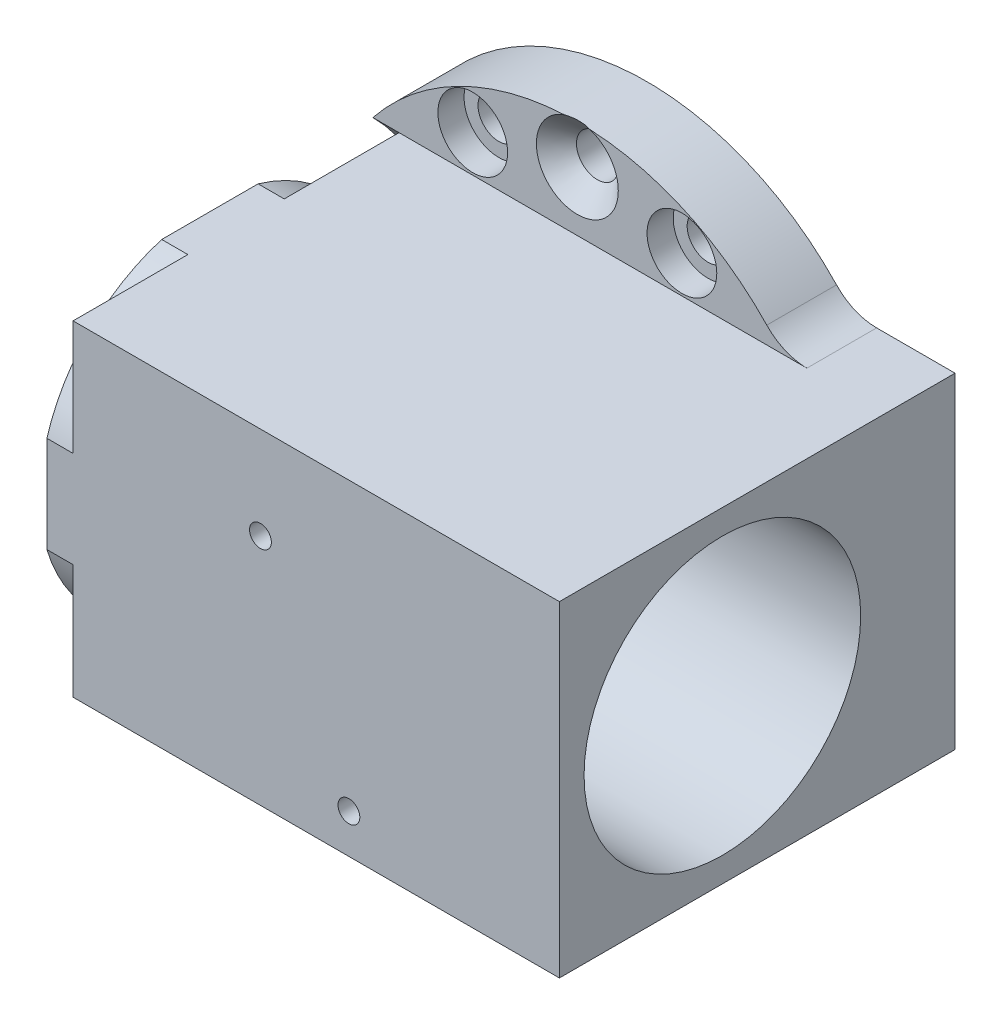
SolidWorks part; units mm, degrees
material "6061 Alloy"
ref_plane "Front" through (0, 0, 0) normal (0, 0, 1) x (1, 0, 0)
ref_plane "Top" through (0, 0, 0) normal (0, 1, 0) x (1, 0, 0)
ref_plane "Right" through (0, 0, 0) normal (1, 0, 0) x (0, 0, -1)
ref_plane "Plane1" through (0, 0, 8) normal (0, 0, 1) x (1, 0, 0)
sketch "Sketch1" plane through (0, 0, 8) normal (0, 0, 1) x (1, 0, 0)
  line L0 (-23.4587, 18.7) -> (-23.4587, -18.7)
  line L1 (23.4587, -18.7) -> (35.3413, -18.7)
  line L2 (35.3413, -18.7) -> (35.3413, 18.7)
  line L3 (35.3413, 18.7) -> (23.4587, 18.7)
  arc A0 (-23.4587, -18.7) -> (23.4587, -18.7) centre (0, 0) ccw
  arc A1 (23.4587, 18.7) -> (-23.4587, 18.7) centre (0, 0) ccw
extrude "Boss-Extrude1" add sketch "Sketch1" against normal blind 8
ref_plane "Plane2" through (-23.4587, 0, 0) normal (-1, 0, 0) x (0, -1, 0)
ref_plane "Plane3" through (-20.4587, 0, 0) normal (1, 0, 0) x (0, 0, -1)
sketch "Sketch3" plane through (-20.4587, 0, 0) normal (1, 0, 0) x (0, 0, -1)
  line L0 (-8, 18.7) -> (-8, -18.7)
  arc A0 (-8, -18.7) -> (-8, 18.7) centre (-26.7, 0) ccw
extrude "Cut-Extrude1" cut sketch "Sketch3" against normal up to surface up to plane "Plane2"
sketch "Sketch4" plane through (0, 0, 8) normal (0, 0, 1) x (1, 0, 0)
  line L0 (-20.4587, 18.7) -> (35.3413, 18.7)
  line L1 (35.3413, 18.7) -> (35.3413, -18.7)
  line L2 (35.3413, -18.7) -> (-20.4587, -18.7)
  line L3 (-20.4587, -18.7) -> (-20.4587, 18.7)
extrude "Boss-Extrude2" add sketch "Sketch4" along normal blind 37.4
sketch "Sketch5" plane through (-20.4587, 0, 0) normal (-1, 0, 0) x (0, 0, 1)
  line L0 (45.4, 18.7) -> (45.4, -18.7)
  line L1 (45.4, -18.7) -> (21.1719, -18.7)
  line L2 (21.1719, 18.7) -> (45.4, 18.7)
  arc A0 (21.1719, -18.7) -> (21.1719, 18.7) centre (26.7, 0) cw
extrude "Boss-Extrude3" add sketch "Sketch5" along normal blind 3
sketch "Sketch6" plane through (-23.4587, 0, 0) normal (-1, 0, 0) x (0, 0, 1)
  line L0 (45.4, -18.7) -> (45.4, -5.5281)
  line L1 (32.2281, -18.7) -> (45.4, -18.7)
  arc A0 (45.4, -5.5281) -> (32.2281, -18.7) centre (26.7, 0) cw
extrude "Cut-Extrude2" cut sketch "Sketch6" against normal blind 3
sketch "Sketch7" plane through (-23.4587, 0, 0) normal (-1, 0, 0) x (0, 0, 1)
  line L0 (45.4, 18.7) -> (32.2281, 18.7)
  line L1 (45.4, 5.5281) -> (45.4, 18.7)
  arc A0 (32.2281, 18.7) -> (45.4, 5.5281) centre (26.7, 0) cw
extrude "Cut-Extrude3" cut sketch "Sketch7" against normal blind 3
ref_plane "Plane4" through (0, 0, 26.7) normal (0, 0, 1) x (1, 0, 0)
sketch "Sketch8" plane through (0, 0, 26.7) normal (0, 0, 1) x (1, 0, 0)
  line L0 (-23.4587, 15.8686) -> (-23.4587, 0)
  line L1 (-23.4587, 0) -> (35.3413, 0)
  line L2 (35.3413, 0) -> (35.3413, 15.8687)
  line L3 (35.3413, 15.8687) -> (9.9413, 15.8687)
  line L4 (9.9413, 15.8687) -> (9.9413, 13.5)
  line L5 (9.9413, 13.5) -> (1.9413, 13.5)
  line L6 (1.9413, 13.5) -> (1.9413, 15.8686)
  line L7 (1.9413, 15.8686) -> (-23.4587, 15.8686)
  line L8 (-23.4587, 0) -> (35.3413, 0) construction
revolve "Cut-Revolve1" cut sketch "Sketch8" angle 360 about L8
hole_wizard "M4x0.7 Tapped Hole1" positions "Sketch10" profile "Sketch9" tap size "M4x0.7" standard "ANSI Metric"
sketch "Sketch10" plane through (0, -18.7, 0) normal (0, -1, 0) x (-1, 0, 0)
  point P0 (12.4587, -39.4)
  point P1 (-29.4413, -39.4)
  point P2 (-29.4413, -5.9)
sketch "Sketch9" plane through (-12.4587, -18.7, 39.4) normal (1, 0, 0) x (0, 0, -1)
  line L0 (0, 0) -> (0, 6.9914)
  line L1 (0, 6.9914) -> (1.65, 6)
  line L2 (1.65, 6) -> (1.65, 0)
  line L5 (1.65, 0) -> (0, 0)
  line L10 (0, 6.9914) -> (-1.65, 6) construction
  line L11 (0, -6.35) -> (0, 107.95) construction
  dimension "Tap Drill Dia." = 3.3
  dimension "Tap Drill Depth" = 6
  dimension "Drill Angle" = 118
hole_wizard "CSK for M4 Flat Head Machine Screw1" positions "Sketch12" profile "Sketch11" countersink size "M4" standard "ANSI Metric" end condition through all
sketch "Sketch12" plane through (0, 0, 8) normal (0, 0, 1) x (1, 0, 0)
  point P0 (0, -25.5)
  point P1 (0, 25.5)
sketch "Sketch11" plane through (0, -25.5, 8) normal (1, 0, 0) x (0, -1, 0)
  line L0 (0, 0) -> (0, 8)
  line L1 (0, 8) -> (2.4, 8)
  line L2 (2.4, 8) -> (2.4, 2.3)
  line L3 (2.4, 2.3) -> (4.7, 0)
  line L5 (4.7, 0) -> (0, 0)
  line L6 (-2.4, 2.3) -> (-4.7, 0) construction
  line L11 (0, -6.35) -> (0, 107.95) construction
  dimension "Thru Hole Dia." = 4.8
  dimension "Thru Hole Depth" = 8
  dimension "Near C'Sink Dia." = 9.4
  dimension "Near C'Sink Angle" = 90
hole_wizard "CBORE for M4 SHCS1" positions "Sketch14" profile "Sketch13" counterbore size "M4" standard "ANSI Metric" end condition through all
sketch "Sketch14" plane through (0, 0, 8) normal (0, 0, 1) x (1, 0, 0)
  point P0 (-12, -22.95)
  point P1 (12, -22.95)
  point P2 (12, 22.95)
  point P3 (-12, 22.95)
sketch "Sketch13" plane through (-12, -22.95, 8) normal (1, 0, 0) x (0, -1, 0)
  line L0 (0, 0) -> (0, 8)
  line L1 (0, 8) -> (2.4, 8)
  line L3 (2.4, 8) -> (2.4, 3)
  line L4 (2.4, 3) -> (4, 3)
  line L5 (4, 3) -> (4, 0)
  line L7 (4, 0) -> (0, 0)
  line L11 (0, -6.35) -> (0, 107.95) construction
  dimension "Thru Hole Dia." = 4.8
  dimension "Thru Hole Depth" = 8
  dimension "C'Bore Dia." = 8
  dimension "C'Bore Depth" = 3
hole_wizard "M3x0.5 Tapped Hole1" positions "Sketch16" profile "Sketch15" tap size "M3x0.5" standard "ANSI Metric"
sketch "Sketch16" plane through (0, 0, 45.4) normal (0, 0, 1) x (1, 0, 0)
  point P0 (1.0413, 8.0737)
  point P1 (11.1917, -14.199)
sketch "Sketch15" plane through (1.0413, 8.0737, 45.4) normal (1, 0, 0) x (0, -1, 0)
  line L0 (0, 0) -> (0, 4.7511)
  line L1 (0, 4.7511) -> (1.25, 4)
  line L2 (1.25, 4) -> (1.25, 0)
  line L5 (1.25, 0) -> (0, 0)
  line L10 (0, 4.7511) -> (-1.25, 4) construction
  line L11 (0, -6.35) -> (0, 107.95) construction
  dimension "Tap Drill Dia." = 2.5
  dimension "Tap Drill Depth" = 4
  dimension "Drill Angle" = 118
fillet "Fillet1" radius 6.35 2 edges at (23.4587, 18.7, 4) (23.4587, -18.7, 4)
sketch "Sketch17" plane through (0, 0, 0) normal (0, 1, 0) x (1, 0, 0)
  line L0 (-23.4587, -26.7) -> (96.3592, -26.7) construction
  line L1 (-23.4587, -32.2281) -> (-23.4587, -21.1719) construction
